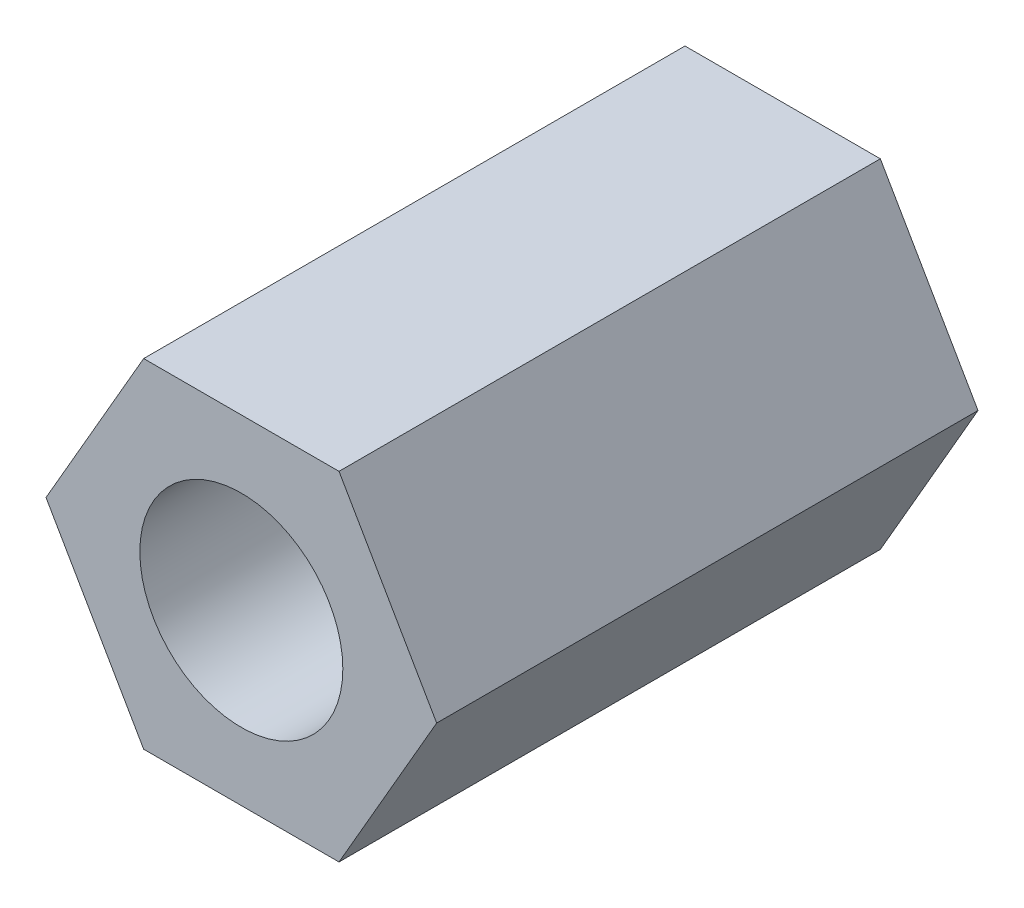
SolidWorks part; units mm, degrees
ref_plane "Plan de face" through (0, 0, 0) normal (0, 0, 1) x (1, 0, 0)
ref_plane "Plan de dessus" through (0, 0, 0) normal (0, 1, 0) x (1, 0, 0)
ref_plane "Plan de droite" through (0, 0, 0) normal (1, 0, 0) x (0, 0, -1)
sketch "Esquisse1" plane through (0, 0, 0) normal (0, 0, 1) x (1, 0, 0)
  line L1 (-2.8868, 0) -> (-1.4434, -2.5)
  line L2 (-1.4434, -2.5) -> (1.4434, -2.5)
  line L3 (1.4434, -2.5) -> (2.8868, 0)
  line L4 (2.8868, 0) -> (1.4434, 2.5)
  line L5 (1.4434, 2.5) -> (-1.4434, 2.5)
  line L6 (-1.4434, 2.5) -> (-2.8868, 0)
  circle A0 centre (0, 0) radius 1.5
  circle A1 centre (0, 0) radius 2.5 construction
  dimension "D1" = 3
  dimension "D2" = 5
extrude "Boss.-Extru.1" add sketch "Esquisse1" along normal blind 8
